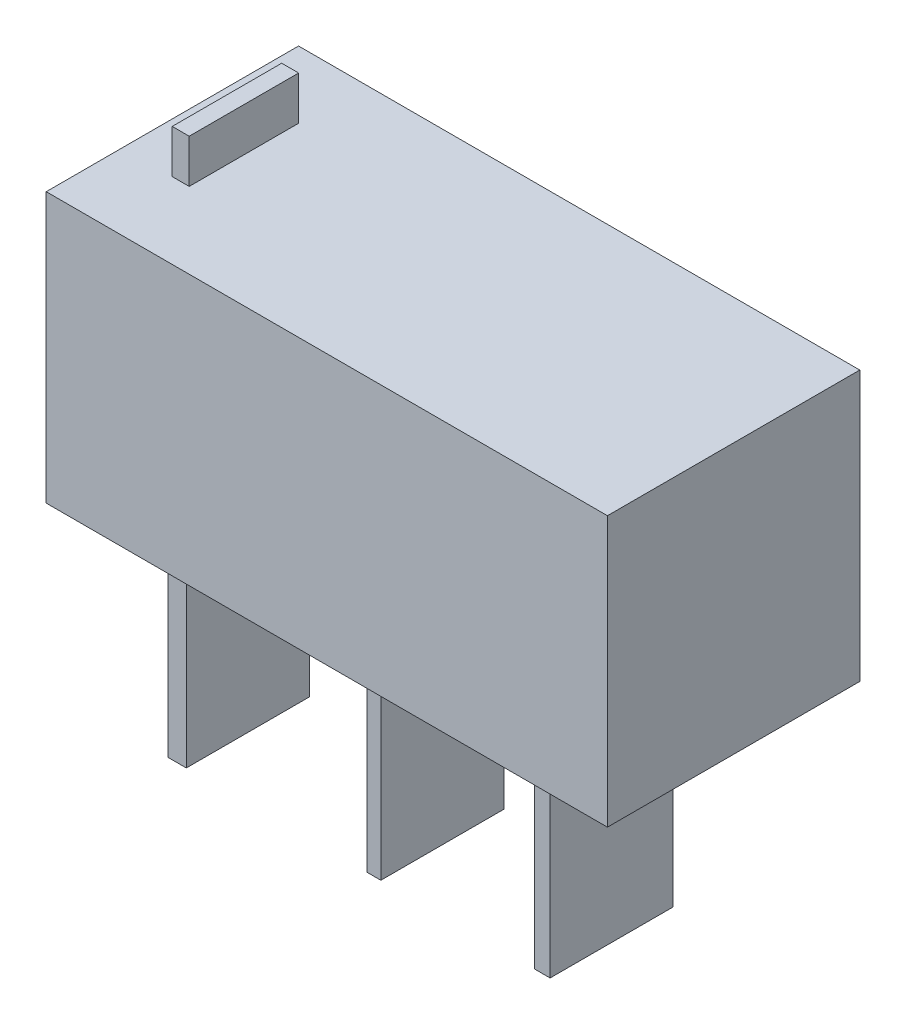
SolidWorks part; units mm, degrees
ref_plane "Front Plane" through (0, 0, 0) normal (0, 0, 1) x (1, 0, 0)
ref_plane "Top Plane" through (0, 0, 0) normal (0, 1, 0) x (1, 0, 0)
ref_plane "Right Plane" through (0, 0, 0) normal (1, 0, 0) x (0, 0, -1)
sketch "Sketch1" plane through (0, 0, 0) normal (0, 1, 0) x (1, 0, 0)
  line L1 (0, 0) -> (12.9, 0)
  line L2 (0, 0) -> (0, -5.8)
  line L3 (0, -5.8) -> (12.9, -5.8)
  line L4 (12.9, 0) -> (12.9, -5.8)
  dimension "D1" = 5.8
  dimension "D2" = 12.9
extrude "Boss-Extrude1" add sketch "Sketch1" along normal blind 6.2
sketch "Sketch2" plane through (0, 6.2, 0) normal (0, 1, 0) x (1, 0, 0)
  line L1 (1.1486, -1.5362) -> (1.5386, -1.5362)
  line L2 (1.1486, -1.5362) -> (1.1486, -4.0521)
  line L3 (1.1486, -4.0521) -> (1.5386, -4.0521)
  line L4 (1.5386, -1.5362) -> (1.5386, -4.0521)
extrude "Boss-Extrude2" add sketch "Sketch2" along normal blind 1
sketch "Sketch3" plane through (0, 0, 0) normal (0, -1, 0) x (-1, 0, 0)
  line L1 (-1.4641, -1.6358) -> (-1.882, -1.6358)
  line L2 (-1.4641, -1.6358) -> (-1.4641, -4.4616)
  line L3 (-1.4641, -4.4616) -> (-1.882, -4.4616)
  line L4 (-1.882, -1.6358) -> (-1.882, -4.4616)
  line L5 (-6.0363, -1.6358) -> (-6.3532, -1.6358)
  line L6 (-6.0363, -1.6358) -> (-6.0363, -4.4616)
  line L7 (-6.0363, -4.4616) -> (-6.3532, -4.4616)
  line L8 (-6.3532, -1.6358) -> (-6.3532, -4.4616)
  line L9 (-9.8867, -1.6358) -> (-10.2436, -1.6358)
  line L10 (-9.8867, -1.6358) -> (-9.8867, -4.4616)
  line L11 (-9.8867, -4.4616) -> (-10.2436, -4.4616)
  line L12 (-10.2436, -1.6358) -> (-10.2436, -4.4616)
extrude "Boss-Extrude3" add sketch "Sketch3" along normal blind 5
